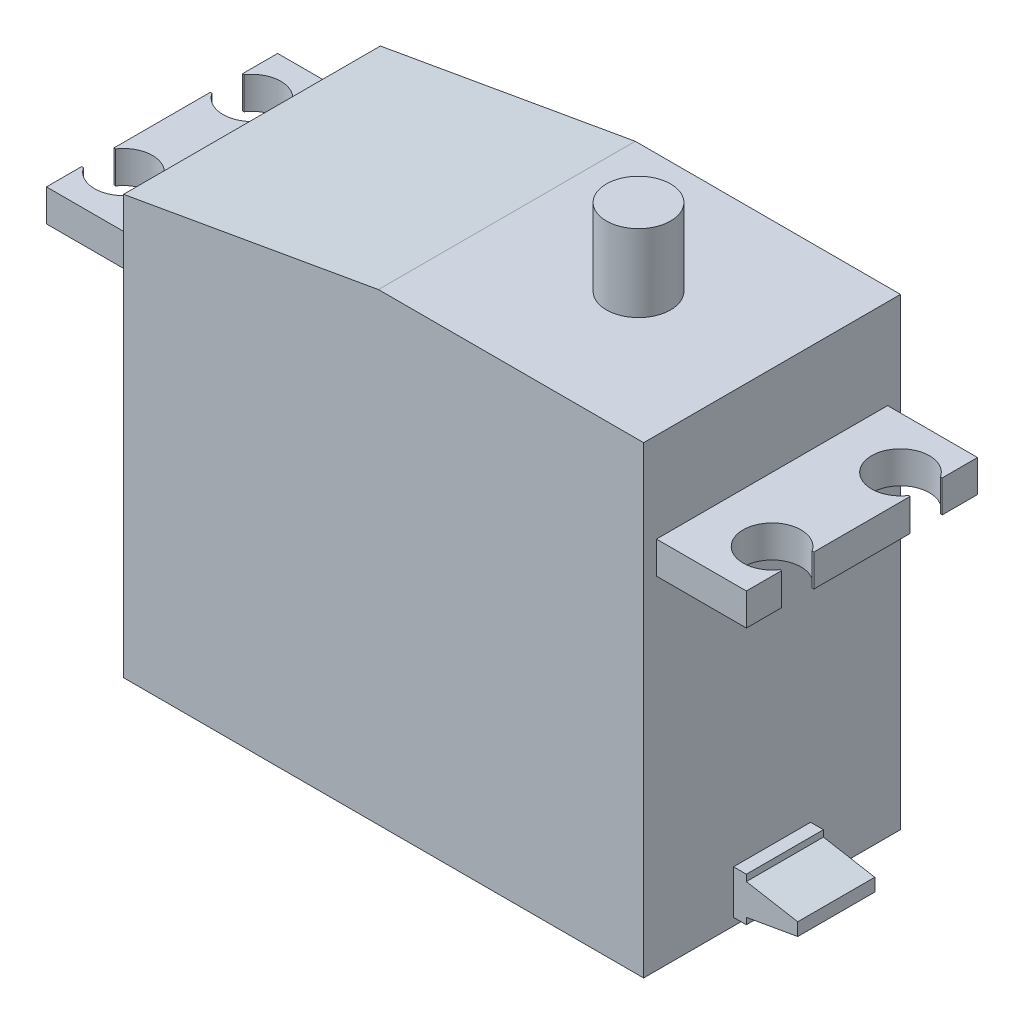
SolidWorks part; units mm, degrees
ref_plane "Front" through (0, 0, 0) normal (0, 0, 1) x (1, 0, 0)
ref_plane "Top" through (0, 0, 0) normal (0, 1, 0) x (1, 0, 0)
ref_plane "Right" through (0, 0, 0) normal (1, 0, 0) x (0, 0, -1)
sketch "Sketch1" plane through (0, 0, 0) normal (0, 0, 1) x (1, 0, 0)
  line L20 (0, 0) -> (40.5, 0)
  line L21 (0, 0) -> (0, 36.1)
  line L22 (0, 36.1) -> (40.5, 36.1)
  line L23 (40.5, 0) -> (40.5, 36.1)
  dimension "D1" = 36.1
  dimension "D2" = 40.5
extrude "Boss-Extrude1" add sketch "Sketch1" along normal blind 20
sketch "Sketch2" plane through (0, 0, 20) normal (0, 0, 1) x (1, 0, 0)
  line L0 (20.25, 0) -> (20.25, 36.1) construction
  line L1 (0, 0) -> (40.5, 0) construction
  line L2 (40.5, 36.1) -> (0, 36.1) construction
  line L3 (0, 26.6) -> (-7, 26.6)
  line L4 (0, 36.1) -> (0, 0) construction
  line L5 (-7, 26.6) -> (-7, 29.1)
  line L6 (-7, 29.1) -> (0, 29.1)
  line L7 (0, 29.1) -> (0, 26.6)
  line L8 (40.5, 29.1) -> (40.5, 26.6)
  line L9 (47.5, 29.1) -> (40.5, 29.1)
  line L10 (47.5, 26.6) -> (47.5, 29.1)
  line L11 (40.5, 26.6) -> (47.5, 26.6)
  dimension "D1" = 2.5
  dimension "D2" = 26.6
  dimension "D3" = 7
extrude "Boss-Extrude2" add sketch "Sketch2" against normal blind 18 from offset 1 offset against normal yes
sketch "Sketch3" plane through (0, 29.1, 0) normal (0, 1, 0) x (1, 0, 0)
  line L0 (20.25, 0) -> (20.25, -20) construction
  line L1 (40.5, 0) -> (0, 0) construction
  line L2 (40.5, -20) -> (0, -20) construction
  line L3 (-7, -10) -> (47.5, -10) construction
  line L4 (-7, -1) -> (-7, -19) construction
  line L5 (47.5, -1) -> (47.5, -19) construction
  line L6 (-6.8708, -3.75) -> (-7, -3.75)
  line L7 (-7, -3.75) -> (-7, -6.25)
  line L8 (-7, -6.25) -> (-6.8708, -6.25)
  line L9 (-7, -13.75) -> (-6.8708, -13.75)
  line L10 (-7, -16.25) -> (-7, -13.75)
  line L11 (-6.8708, -16.25) -> (-7, -16.25)
  line L12 (47.3708, -16.25) -> (47.5, -16.25)
  line L13 (47.5, -16.25) -> (47.5, -13.75)
  line L14 (47.5, -13.75) -> (47.3708, -13.75)
  line L15 (47.5, -6.25) -> (47.3708, -6.25)
  line L16 (47.5, -3.75) -> (47.5, -6.25)
  line L17 (47.3708, -3.75) -> (47.5, -3.75)
  arc A0 (-6.8708, -6.25) -> (-6.8708, -3.75) centre (-5, -5) ccw
  arc A1 (-6.8708, -13.75) -> (-6.8708, -16.25) centre (-5, -15) cw
  arc A2 (47.3708, -13.75) -> (47.3708, -16.25) centre (45.5, -15) ccw
  arc A3 (47.3708, -6.25) -> (47.3708, -3.75) centre (45.5, -5) cw
  point P16 (0, 0)
  dimension "D1" = 4.5
  dimension "D2" = 25.25
  dimension "D3" = 5
  dimension "D4" = 2.5
extrude "Cut-Extrude1" cut sketch "Sketch3" against normal up to next
sketch "Sketch4" plane through (0, 36.1, 0) normal (0, 1, 0) x (1, 0, 0)
  line L0 (40.5, -1) -> (40.5, -19) construction
  line L1 (40.5, -20) -> (40.5, 0) construction
  circle A0 centre (30.1, -10) radius 2.5
  point P2 (0, 0)
  point P5 (40.5, -10)
  dimension "D2" = 5
  dimension "D1" = 10.4
extrude "Boss-Extrude3" add sketch "Sketch4" along normal blind 6
sketch "Sketch5" plane through (0, 0, 20) normal (0, 0, 1) x (1, 0, 0)
  line L0 (40.5, 4) -> (41.5, 4)
  line L1 (40.5, 0) -> (40.5, 36.1) construction
  line L2 (41.5, 4) -> (41.5, 3.5)
  line L3 (41.5, 3.5) -> (45.5, 2.7947)
  line L4 (45.5, 2.7947) -> (45.5, 1.7947)
  line L5 (45.5, 2.2947) -> (40.5, 2.2947) construction
  line L6 (0, 0) -> (40.5, 0) construction
  line L7 (41.5, 1.0894) -> (45.5, 1.7947)
  line L8 (41.5, 0.5894) -> (41.5, 1.0894)
  line L9 (40.5, 0.5894) -> (41.5, 0.5894)
  line L10 (40.5, 0.5894) -> (40.5, 4)
  dimension "D1" = 1
  dimension "D2" = 0.5
  dimension "D3" = 260
  dimension "D4" = 5
  dimension "D5" = 4
  dimension "D6" = 0.5
extrude "Boss-Extrude4" add sketch "Sketch5" against normal blind 6 from offset 7 offset against normal yes
sketch "Sketch6" plane through (0, 0, 20) normal (0, 0, 1) x (1, 0, 0)
  line L0 (0, 32.6) -> (19.8495, 36.1)
  line L1 (19.8495, 36.1) -> (0, 36.1)
  line L2 (0, 36.1) -> (0, 32.6)
  line L3 (0, 29.1) -> (-7, 29.1) construction
  line L4 (40.5, 36.1) -> (0, 36.1) construction
  line L5 (0, 36.1) -> (0, 0) construction
  point P7 (15.1852, 36.1)
  dimension "D1" = 80
  dimension "D2" = 3.5
extrude "Cut-Extrude2" cut sketch "Sketch6" against normal up to next
